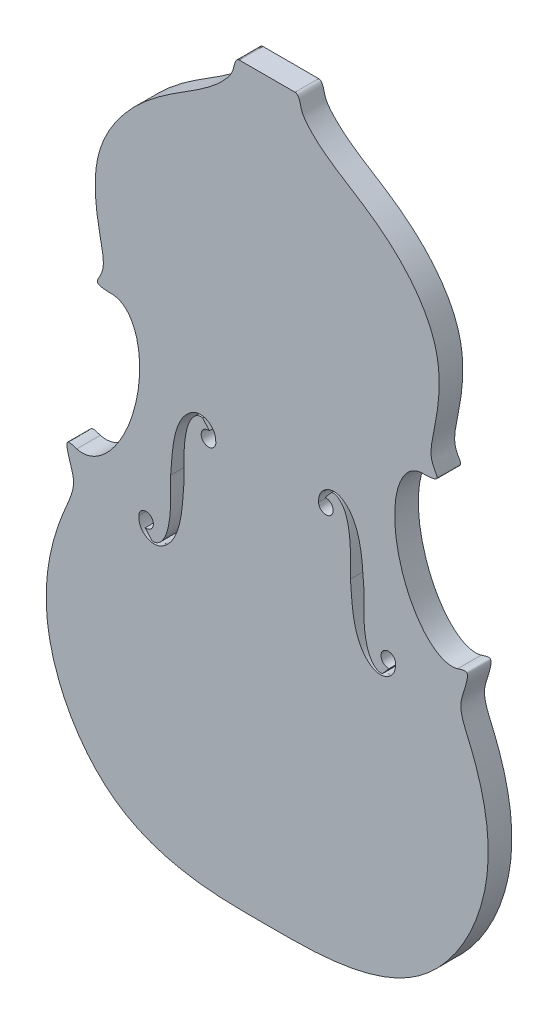
SolidWorks part; units mm, degrees
ref_plane "Front Plane" through (0, 0, 0) normal (0, 0, 1) x (1, 0, 0)
ref_plane "Top Plane" through (0, 0, 0) normal (0, 1, 0) x (1, 0, 0)
ref_plane "Right Plane" through (0, 0, 0) normal (1, 0, 0) x (0, 0, -1)
sketch "SketchPictureFront" plane through (0, 0, 0) normal (0, 0, 1) x (1, 0, 0)
  line L0 (-151.7172, 1634.9996) -> (638.2828, 1634.9996) construction
sketch "SketchPictureRight" plane through (0, 0, 0) normal (1, 0, 0) x (0, 0, -1)
  line L0 (-135.6802, 1539.0324) -> (654.3198, 1539.0324) construction
sketch "Sketch5" plane through (0, 0, 0) normal (0, 0, 1) x (1, 0, 0)
  line L0 (0, -554.9675) -> (0, 489.2296)
  line L1 (0, 489.2296) -> (39.526, 489.2296)
  line L2 (0, -554.9675) -> (-33.986, -554.9675) construction
  ellipse E0 centre (241.7303, 2.8151) end of major axis (269.6363, -104.5255) minor radius 55.6713 construction
  ellipse E1 centre (241.7303, 2.8151) end of major axis (269.6363, -104.5255) minor radius 55.6713 (270.371, -104.3238) -> (219.9912, 111.0476) cw
  spline S0 degree 3 poles (39.526, 489.2296) (41.9942, 489.2296) (46.5805, 483.709) (47.7623, 469.5398) (74.7703, 435.7587) (127.3468, 407.1292) (196.1476, 356.2641) (250.1218, 278.7198) (243.797, 200.2598) (231.4006, 148.6678) (233.2066, 129.4739) (246.1061, 111.4569) (223.5505, 111.0135) (219.9912, 111.0476) knots 0 0 0 0 0.004293 0.013713 0.029409 0.0918 0.139495 0.210643 0.278267 0.300685 0.318441 0.325162 0.331714 0.331714 0.331714 0.331714
  spline S1 degree 3 poles (270.371, -104.3238) (281.7873, -100.433) (286.6653, -102.9744) (280.0534, -125.9482) (270.8406, -151.6625) (307.7622, -226.6933) (330.7687, -359.3259) (234.5166, -526.5754) (103.9803, -554.0297) (29.3141, -555.0293) (6.9539, -554.9675) (0, -554.9675) knots 0.531516 0.531516 0.531516 0.531516 0.541192 0.55587 0.57021 0.600542 0.716993 0.8491 0.951451 0.984335 1 1 1 1
extrude "Boss-Extrude1" add sketch "Sketch5" against normal blind 33.528 contours S0 E1 S1 L0 L1
mirror "Mirror1" about plane through (0, -554.9675, -33.528) normal (1, 0, 0) of bodies 101
sketch "Sketch6" plane through (0, 0, 0) normal (0, 0, 1) x (1, 0, 0)
  line L0 (137.1711, -39.8882) -> (137.1711, -99.2084) construction
  line L1 (51.6913, -70.2706) -> (209.5215, -70.2706) construction
  line L2 (82.1137, 12.1746) -> (91.4952, 23.0675)
  line L4 (173.2319, -152.7158) -> (163.8504, -163.6087)
  arc A0 (72.9573, 1.8633) -> (82.1137, 12.1746) centre (83.3414, 1.8633) ccw
  arc A1 (182.3884, -142.4045) -> (173.2319, -152.7158) centre (172.0043, -142.4045) ccw
  spline S0 degree 3 poles (72.9573, 1.8633) (72.9573, 6.1022) (74.4269, 15.9218) (85.4143, 25.0585) (100.1068, 26.7423) (117.9521, 15.9224) (134.841, -18.4126) (135.3341, -49.9523) (137.1711, -70.2706) knots 0 0 0 0 0.082676 0.195735 0.255854 0.372642 0.585943 1 1 1 1
  spline S1 degree 3 poles (91.4952, 23.0675) (98.1534, 24.846) (108.559, 15.3325) (120.1766, -17.5232) (117.8627, -47.4776) (118.1745, -70.2706) knots 0 0 0 0 0.180443 0.343565 1 1 1 1
  spline S2 degree 3 poles (182.3884, -142.4045) (182.3884, -146.6434) (180.9187, -156.463) (169.9314, -165.5997) (155.2388, -167.2836) (137.3935, -156.4636) (120.5046, -122.1286) (120.0115, -90.5889) (118.1745, -70.2706) knots 0 0 0 0 0.082676 0.195735 0.255854 0.372642 0.585943 1 1 1 1
  spline S3 degree 3 poles (163.8504, -163.6087) (157.1922, -165.3872) (146.7867, -155.8738) (135.169, -123.018) (137.483, -93.0636) (137.1711, -70.2706) knots 0 0 0 0 0.180443 0.343565 1 1 1 1
  point P32 (0, 0)
  point P37 (0, 0)
extrude "Cut-Extrude1" cut sketch "Sketch6" against normal through all both and the other way through all contours S1 S2 A1 L4 S3 S0 A0 L2
mirror "Mirror3" about plane through (0, 0, 0) normal (1, 0, 0) of "Cut-Extrude1"
